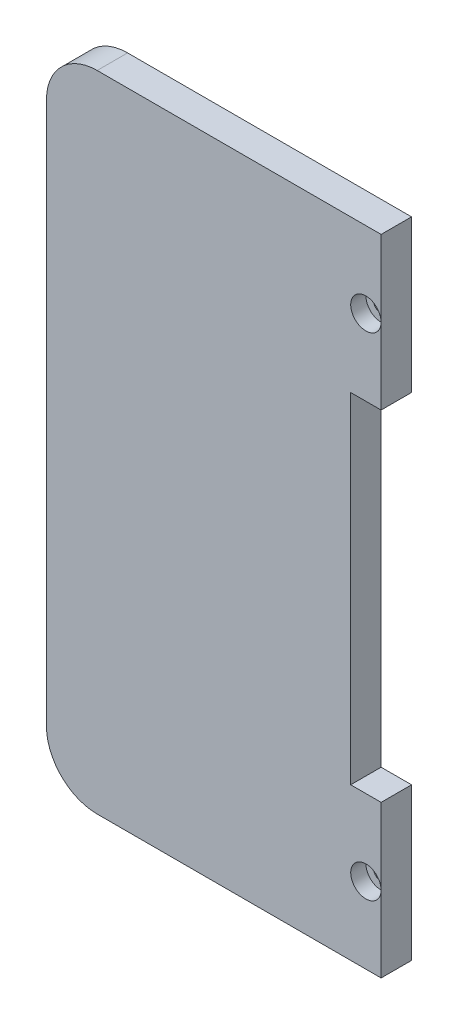
SolidWorks part; units mm, degrees
ref_plane "Plan de face" through (0, 0, 0) normal (0, 0, 1) x (1, 0, 0)
ref_plane "Plan de dessus" through (0, 0, 0) normal (0, 1, 0) x (1, 0, 0)
ref_plane "Plan de droite" through (0, 0, 0) normal (1, 0, 0) x (0, 0, -1)
sketch "Esquisse1" plane through (0, 0, 0) normal (0, 0, 1) x (1, 0, 0)
  line L1 (-33, 63.5) -> (33, 63.5)
  line L2 (-33, 63.5) -> (-33, -63.5)
  line L3 (-33, -63.5) -> (33, -63.5)
  line L4 (33, 63.5) -> (33, -63.5)
  line L5 (-33, 63.5) -> (33, -63.5) construction
  line L6 (-33, -63.5) -> (33, 63.5) construction
  point P0 (0, 0)
  dimension "D1" = 66
  dimension "D2" = 127
extrude "Boss.-Extru.1" add sketch "Esquisse1" along normal blind 6
fillet "Congé1" radius 10 2 edges at (-33, 63.5, 3) (-33, -63.5, 3)
sketch "Esquisse2" plane through (0, 0, 0) normal (0, 0, -1) x (-1, 0, 0)
  line L0 (-33, -63.5) -> (-33, 63.5) construction
  line L1 (23, -63.5) -> (-33, -63.5) construction
  line L2 (-33, 63.5) -> (23, 63.5) construction
  line L3 (-33, 63.5) -> (23, 63.5) construction
  line L11 (-30, 0) -> (-42.007, 0) construction
  line L13 (-27, -33.5) -> (-33, -33.5)
  line L14 (-27, -33.5) -> (-27, 33.5)
  line L15 (-27, 33.5) -> (-33, 33.5)
  line L16 (-33, -33.5) -> (-33, 33.5)
  circle A0 centre (-30, -48.5) radius 1.5
  circle A1 centre (-30, 48.5) radius 1.5
  dimension "D6" = 15
  dimension "D4" = 3
  dimension "D8" = 15
  dimension "D1" = 67
  dimension "D2" = 30
  dimension "D3" = 6
  dimension "D5" = 3
  dimension "D7" = 30
  dimension "D9" = 15
  dimension "D10" = 15
extrude "Enlèv. mat.-Extru.1" cut sketch "Esquisse2" against normal through all
sketch "Esquisse5" plane through (0, 0, 6) normal (0, 0, 1) x (1, 0, 0)
  circle A0 centre (30, 48.5) radius 2.995
  circle A1 centre (30, -48.5) radius 2.995
  dimension "D1" = 5.99
  dimension "D2" = 5.99
extrude "Enlèv. mat.-Extru.4" cut sketch "Esquisse5" against normal blind 3
